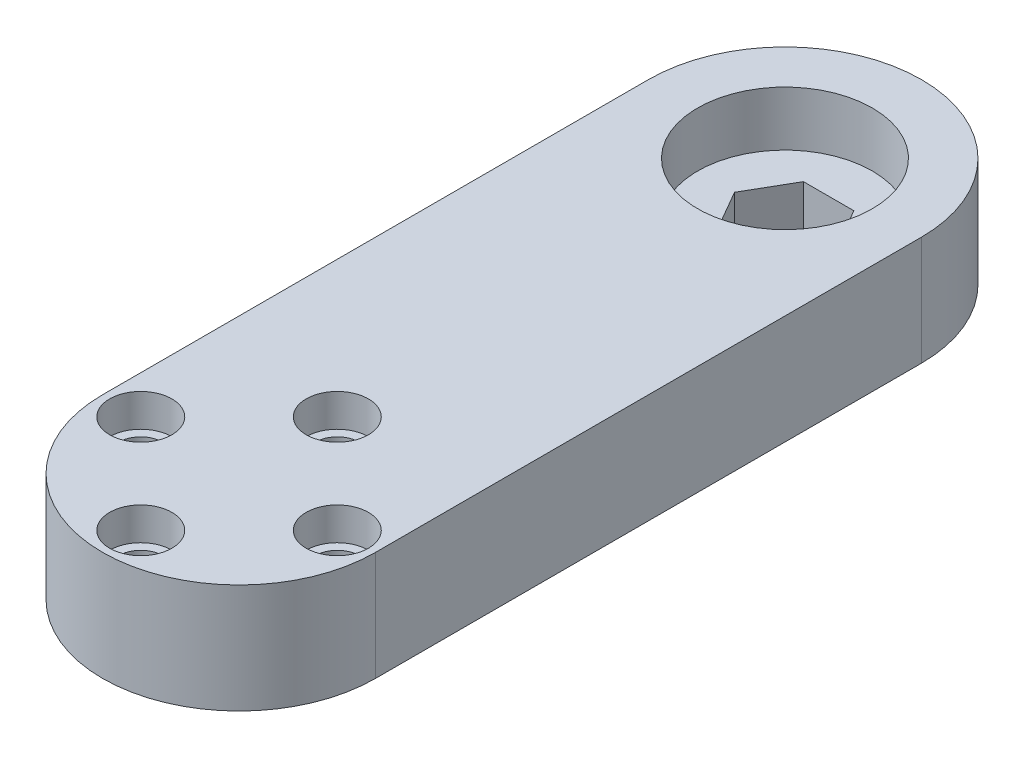
SolidWorks part; units mm, degrees
ref_plane "Front Plane" through (0, 0, 0) normal (0, 0, 1) x (1, 0, 0)
ref_plane "Top Plane" through (0, 0, 0) normal (0, 1, 0) x (1, 0, 0)
ref_plane "Right Plane" through (0, 0, 0) normal (1, 0, 0) x (0, 0, -1)
sketch "Sketch1" plane through (0, 0, 0) normal (0, 1, 0) x (1, 0, 0)
  line L0 (0, 0) -> (-38918.2376, 0) construction
  line L1 (0, 0) -> (0, -38918.2376) construction
  line L2 (-12.5, 0) -> (-12.5, 50)
  line L4 (12.5, 0) -> (12.5, 50)
  arc A0 (-12.5, 0) -> (12.5, 0) centre (0, 0) ccw
  arc A1 (12.5, 50) -> (-12.5, 50) centre (0, 50) ccw
  point P11 (0, 125)
  dimension "D1" = 25
  dimension "D3" = 12.5
  dimension "D2" = 50
extrude "Boss-Extrude1" add sketch "Sketch1" along normal blind 10
sketch "Sketch2" plane through (0, 10, 0) normal (0, 1, 0) x (1, 0, 0)
  line L0 (0, 0) -> (-50000, 0) construction
  line L1 (0, 0) -> (0, -50000) construction
  circle A0 centre (0, 0) radius 9 construction
  circle A1 centre (0, 9) radius 2.85
  circle A2 centre (9, 0) radius 2.85
  circle A3 centre (0, -9) radius 2.85
  circle A4 centre (-9, 0) radius 2.85
  point P18 (0, 0)
  dimension "D1" = 18
  dimension "D2" = 5.7
  dimension "D3" = 4
extrude "Cut-Extrude1" cut sketch "Sketch2" against normal blind 3
sketch "Sketch3" plane through (0, 10, 0) normal (0, 1, 0) x (1, 0, 0)
  line L0 (0, 0) -> (-50000, 0) construction
  line L1 (0, 0) -> (0, -50000) construction
  circle A1 centre (0, 9) radius 2
  circle A2 centre (9, 0) radius 2
  circle A3 centre (0, -9) radius 2
  circle A4 centre (-9, 0) radius 2
  point P17 (0, 0)
  dimension "D1" = 4
  dimension "D2" = 4
extrude "Cut-Extrude2" cut sketch "Sketch3" against normal through all
sketch "Sketch4" plane through (0, 10, 0) normal (0, -1, 0) x (1, 0, 0)
  line L0 (0, 0) -> (0, -50000) construction
  line L1 (0, -50) -> (-50000, -50) construction
  circle A6 centre (0, -50) radius 8
  dimension "D1" = 16
extrude "Cut-Extrude5" cut sketch "Sketch4" along normal blind 5 contours A6
sketch "Sketch6" plane through (0, 10, 0) normal (0, 1, 0) x (1, 0, 0)
  line L0 (0, 0) -> (0, 50000) construction
  line L1 (0, 50) -> (-50000, 50) construction
  circle A0 centre (0, 50) radius 3.5
  dimension "D1" = 7
extrude "Cut-Extrude6" cut sketch "Sketch6" against normal through all
sketch "Sketch7" plane through (0, 0, 0) normal (0, -1, 0) x (1, 0, 0)
  line L0 (0, 0) -> (0, -50000) construction
  line L1 (0, 0) -> (-50000, 0) construction
  line L2 (0, -50) -> (-50000, -50) construction
  line L4 (4.6188, -50) -> (2.3094, -46)
  line L5 (2.3094, -46) -> (-2.3094, -46)
  line L6 (-2.3094, -46) -> (-4.6188, -50)
  line L7 (-4.6188, -50) -> (-2.3094, -54)
  line L8 (-2.3094, -54) -> (2.3094, -54)
  line L9 (2.3094, -54) -> (4.6188, -50)
  circle A1 centre (0, -50) radius 4 construction
  dimension "D1" = 8
extrude "Cut-Extrude7" cut sketch "Sketch7" against normal through all
